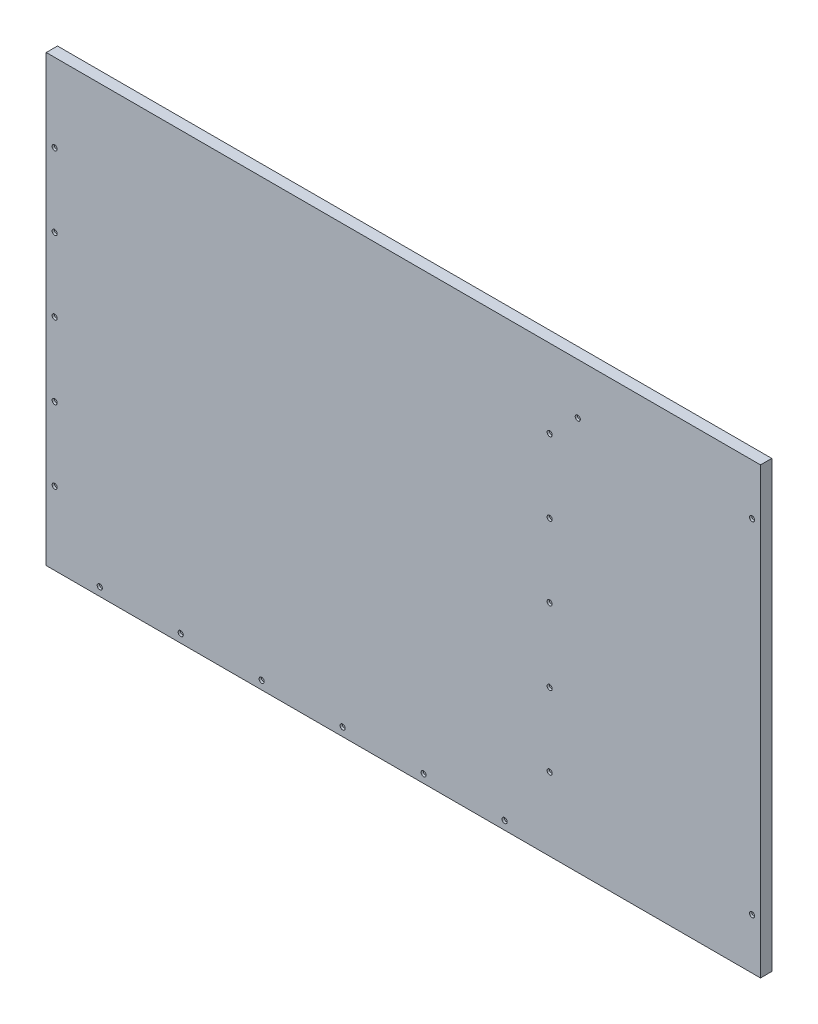
SolidWorks part; units mm, degrees
ref_plane "Front Plane" through (0, 0, 0) normal (0, 0, 1) x (1, 0, 0)
ref_plane "Top Plane" through (0, 0, 0) normal (0, 1, 0) x (1, 0, 0)
ref_plane "Right Plane" through (0, 0, 0) normal (1, 0, 0) x (0, 0, -1)
sketch "Sketch1" plane through (0, 0, 0) normal (0, 0, 1) x (1, 0, 0)
  line L1 (403.3266, -250.9266) -> (-403.3266, -250.9266)
  line L2 (403.3266, -250.9266) -> (403.3266, 250.9266)
  line L3 (403.3266, 250.9266) -> (-403.3266, 250.9266)
  line L4 (-403.3266, -250.9266) -> (-403.3266, 250.9266)
  line L5 (403.3266, -250.9266) -> (-403.3266, 250.9266) construction
  line L6 (403.3266, 250.9266) -> (-403.3266, -250.9266) construction
  point P0 (0, 0)
  dimension "D1" = 501.8532
  dimension "D2" = 806.6532
extrude "Boss-Extrude1" add sketch "Sketch1" along normal blind 12.7
sketch "Sketch2" plane through (0, 0, 12.7) normal (0, 0, 1) x (1, 0, 0)
  line L0 (-403.3266, -231.8766) -> (-393.8016, -231.8766) construction
  line L1 (-403.3266, 250.9266) -> (-403.3266, -250.9266) construction
  line L2 (-393.8016, -168.4782) -> (-393.8016, -250.9266) construction
  line L3 (-403.3266, -250.9266) -> (403.3266, -250.9266) construction
  line L4 (-393.8016, -168.4782) -> (-374.7516, -168.4782) construction
  line L5 (-374.7516, -168.4782) -> (165.2016, -168.4782) construction
  circle A0 centre (-393.8016, -168.4782) radius 2.8956
  circle A1 centre (165.2016, -168.4782) radius 2.8956
  dimension "D4" = 5.7912
  dimension "D1" = 19.05
  dimension "D2" = 63.3984
  dimension "D3" = 9.525
  dimension "D5" = 19.05
  dimension "D6" = 539.9532
extrude "SideBarHoleMaster" cut sketch "Sketch2" against normal through all
sketch "Sketch3" plane through (0, 0, 0) normal (0, 0, -1) x (-1, 0, 0)
  circle A0 centre (-165.2016, -168.4782) radius 6.35
  circle A1 centre (393.8016, -168.4782) radius 6.35
  dimension "D1" = 12.7
extrude "Countersink" cut sketch "Sketch3" against normal offset from surface (10.16 mm away) 2.54 up to face at (168.0972, -168.4782, 12.7)
pattern_linear "LPattern1" count 5 spacing 82.7391 along (0, 1, 0) of "Countersink", "SideBarHoleMaster"
sketch "Sketch4" plane through (0, 0, 12.7) normal (0, 0, 1) x (1, 0, 0)
  line L0 (-403.3266, -241.4016) -> (-342.9, -241.4016) construction
  line L1 (-403.3266, 250.9266) -> (-403.3266, -250.9266) construction
  line L2 (-403.3266, -250.9266) -> (403.3266, -250.9266) construction
  line L3 (-403.3266, -241.4016) -> (-406.4, -241.4016) construction
  circle A0 centre (-342.9, -241.4016) radius 2.8956
  dimension "D1" = 5.7912
  dimension "D2" = 9.525
  dimension "D3" = 3.0734
  dimension "D4" = 63.5
extrude "RearBarMount" cut sketch "Sketch4" against normal through all
sketch "Sketch5" plane through (0, 0, 0) normal (0, 0, -1) x (-1, 0, 0)
  circle A0 centre (342.9, -241.4016) radius 6.35
  circle A1 centre (393.8016, -168.4782) radius 6.35 construction
extrude "RearBarCounterSink" cut sketch "Sketch5" against normal offset from surface (10.16 mm away) 2.54 up to face at (-340.0044, -241.4016, 12.7)
pattern_linear "LPattern2" count 6 spacing 91.44 along (1, 0, 0) of "RearBarMount", "RearBarCounterSink"
sketch "Sketch6" plane through (0, 0, 12.7) normal (0, 0, 1) x (1, 0, 0)
  line L0 (393.8016, -250.9266) -> (393.8016, 193.5734) construction
  line L1 (-403.3266, -250.9266) -> (403.3266, -250.9266) construction
  line L2 (403.3266, -250.9266) -> (403.3266, 250.9266) construction
  line L3 (196.9516, 193.5734) -> (216.0016, 193.5734) construction
  line L4 (216.0016, 193.5734) -> (393.8016, 193.5734) construction
  circle A0 centre (393.8016, 193.5734) radius 2.8956
  circle A1 centre (393.8016, -193.7766) radius 2.8956
  circle A2 centre (196.9516, 193.5734) radius 2.8956
  dimension "D3" = 9.525
  dimension "D1" = 5.7912
  dimension "D2" = 444.5
  dimension "D4" = 57.15
  dimension "D5" = 177.8
  dimension "D6" = 19.05
extrude "EBForwardMountHole" cut sketch "Sketch6" against normal through all
sketch "Sketch7" plane through (0, 0, 0) normal (0, 0, -1) x (-1, 0, 0)
  circle A0 centre (-393.8016, 193.5734) radius 6.35
  circle A1 centre (-393.8016, -193.7766) radius 6.35
  circle A2 centre (-196.9516, 193.5734) radius 6.35
  dimension "D1" = 12.7
extrude "EB-Mounts-Countersinks" cut sketch "Sketch7" against normal offset from surface (10.16 mm away) 2.54 up to face at (396.6972, -193.7766, 12.7)
equation "\"Height\"= 32in"
equation "\"Width\"= 23in"
equation "\"Depth\"= 20in"
equation "\"Plexi\"= .121in"
equation "\"MagnetThickness\"=3mm"
equation "\"MagnetDiameter\"=12mm"
equation "\"DoorPlexi\" = \"Plexi\""
equation "\"BasePlateThickness\" = 0.5in"
equation "\"BasePlateWidth\" = \"Width\"+\"EBWidth\"-2*\"Plexi\""
equation "\"Boxsize\" = .75in"
equation "\"Boxinner\" = .625in"
equation "\"CornerCube\" = 0.75in"
equation "\"FingerLength\" = 1.125in"
equation "\"Cutwidth\"= .016in"
equation "\"Earsize\"= 1in + \"Cutwidth\" /2"
equation "\"Slotsize\" = 1in - \"CutWidth\" / 2"
equation "\"InnerWidth\" = \"Width\" - 2* \"Plexi\""
equation "\"InnerHeight\" = \"Height\" -2 * \"Plexi\""
equation "\"InnerDepth\" = \"Depth\" - 2*\"Plexi\""
equation "\"RearNumHoles\" = 7"
equation "\"RearHolesBorder\" = 2.2"
equation "\"RearHoleSpacing\" = (\"Width\" - 2*\"RearHolesBorder\") / (\"RearNumHoles\"-1)"
equation "\"RearBarLength\" = (\"InnerWidth\"-2*\"CornerCube\")"
equation "\"RearTopNumHoles\" = 6"
equation "\"RearTopHolesBorder\" = 2.5"
equation "\"RearTopHolesSpacing\" = (\"Width\" - 2*\"RearTopHolesBorder\") / (\"RearTopNumHoles\"-1)"
equation "\"SideTopNumHoles\" = 5"
equation "\"SideTopHoleOffset\"=\"CornerCube\"+\"FingerLength\"+\"Plexi\"+.5"
equation "\"SideTopHoleSpacing\" = (\"TopBarDepth\"-2*\"SideTopHoleOffset\") / (\"SideTopNumHoles\"-1)"
equation "\"SideHorizNumHoles\" = 6"
equation "\"SideHorizHoleBorder\" = 2.25"
equation "\"SideHorizHoleSpacing\" = (\"TopBarDepth\"-2*\"SideHorizHoleBorder\") / (\"SideHorizNumHoles\"-1)"
equation "\"SideVertBarLength\"=\"Height\"-\"BasePlateThickness\"-2*\"CornerCube\"-\"Plexi\""
equation "\"SideVertNumHoles\" = 6"
equation "\"SideVertHolesBorder\" = \"CornerCube\"+\"FingerLength\"+.9"
equation "\"SideVertHoleSpacing\" = (\"InnerHeight\" - 2*\"SideVertHolesBorder\") / (\"SideVertNumHoles\"-1)"
equation "\"RearSideVertNumHoles\" = 7"
equation "\"RearSideVertHolesBorder\" = 2.5"
equation "\"RearSideVertHoleSpacing\" = (\"InnerHeight\" - 2*\"RearSideVertHolesBorder\") / (\"RearSideVertNumHoles\"-1)"
equation "\"RivetDia\" = .228in"
equation "\"SlotDepth\" = \"Plexi\" + 0.75in + .005in"
equation "\"SideSlotWidth\"   = \"Plexi\"+.005in"
equation "\"SidePanelVertSpacing\" = (\"Height\"-2*(1.75-\"Plexi\")) / 5"
equation "\"BottomPanelSideHoleSpacing\" = (\"InnerDepth\"-2*(1.75-\"Plexi\")) / 4"
equation "\"FrontDoorGap\" = .1in"
equation "\"TopDepth\" = \"Depth\"-\"DoorPlexi\"-\"FrontDoorGap\""
equation "\"TopBarDepth\" = \"Depth\"-\"DoorPlexi\"-\"Plexi\"-2*\"MagnetThickness\"-2*\"CornerCube\""
equation "\"BasePlateDepth\" = \"Depth\"-\"Plexi\"-\"DoorPlexi\""
equation "\"D1@Sketch1\"=\"BasePlateDepth\""
equation "\"D2@Sketch1\"=\"BasePlateWidth\""
equation "\"D1@Boss-Extrude1\"=\"BasePlateThickness\""
equation "\"EBWidth\" = 9in"
equation "\"BoxsizeHalf\" = \"Boxsize\"/2"
equation "\"FingerWidth\" = .625in"
equation "\"CoolerDepth\" = 12in"
equation "\"ShelfGap\" = 0.5in"
equation "\"ShelfDepth\" = \"TopBarDepth\"+\"CornerCube\"-\"CoolerDepth\""
equation "\"ShelfBarDepth\"=\"ShelfDepth\"-2*\"CornerCube\""
equation "\"ShelfWidth\" = \"EBWidth\"-\"ShelfGap\""
equation "\"ShelfBarWidth\" = \"EBWidth\"-\"Boxsize\""
equation "\"ShelfBarWidthShort\" = \"ShelfBarWidth\"-\"Boxsize\"-\"ShelfGap\""
equation "\"IntakeWidth\"=4in"
equation "\"IntakeHeight\"=2in"
equation "\"ExhaustWidth\"=4in"
equation "\"ExhaustHeight\"=2in"
equation "\"VentSpacing\"=7in"
equation "\"AngleBracketLength\"=20mm"
equation "\"AngleBracketWidth\"=.5in"
equation "\"AngleBracketThickness\"=.125in"
equation "\"AngleBracketHolePos\"=15mm"
equation "\"AngleBracketHoleDia\"=\"Rivet3_16Dia\""
equation "\"ShelfBarAngleHole\"=\"ShelfGap\"+\"Boxsize\"+\"AngleBracketHolePosShort\""
equation "\"D1@Sketch2\"=\"Boxsize\""
equation "\"D2@Sketch2\"=\"SideTopHoleOffset\""
equation "\"D3@Sketch2\"=\"BoxsizeHalf\""
equation "\"ComponentMountDia\"=0.1770"
equation "\"ShelfThickness\" = .220in"
equation "\"BinderPostDia\" = .228in"
equation "\"ShelfHeight1\" = 13in"
equation "\"ShelfHeight2\" = 24in"
equation "\"VentVertLocation\"=12.75in"
equation "\"PSBracketThickness\" = .0641in"
equation "\"D4@Sketch2\"=\"BinderPostDia\""
equation "\"D5@Sketch2\"=\"Boxsize\""
equation "\"D6@Sketch2\"=\"RearBarLength\""
equation "\"D1@LPattern1\"=\"SideTopNumHoles\""
equation "\"D3@LPattern1\"=\"SideTopHoleSpacing\""
equation "\"D1@Sketch4\"=\"BinderPostDia\""
equation "\"D2@Sketch4\"=\"BoxsizeHalf\""
equation "\"D3@Sketch4\"=\"Plexi\""
equation "\"D4@Sketch4\"=\"RearTopHolesBorder\""
equation "\"D3@LPattern2\"=\"RearTopHolesSpacing\""
equation "\"D1@LPattern2\"=\"RearTopNumHoles\""
equation "\"D1@Sketch6\"=\"BinderPostDia\""
equation "\"EBForwardMountOffset\" = 4.0in"
equation "\"EBForwardMount\" = 2*\"Boxsize\"+\"CoolerDepth\"+\"EBForwardMountOffset\""
equation "\"D2@Sketch6\"=\"EBForwardMount\""
equation "\"D3@Sketch6\"=\"BoxsizeHalf\""
equation "\"EBRearwardMountOffset\" = 1.5in"
equation "\"EBRearwardMount\"= \"Boxsize\"+\"EBRearwardMountOffset\""
equation "\"D4@Sketch6\"=\"EBRearwardMount\""
equation "\"D5@Sketch6\"=\"ShelfBarWidthShort\""
equation "\"D6@Sketch6\"=\"Boxsize\""
